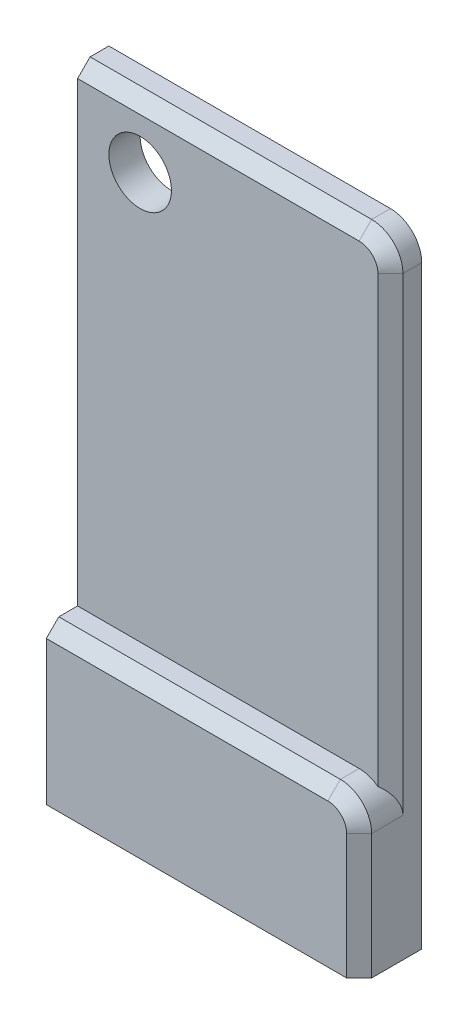
SolidWorks part; units mm, degrees
material "1060 Alloy"
ref_plane "Front Plane" through (0, 0, 0) normal (0, 0, 1) x (1, 0, 0)
ref_plane "Top Plane" through (0, 0, 0) normal (0, 1, 0) x (1, 0, 0)
ref_plane "Right Plane" through (0, 0, 0) normal (1, 0, 0) x (0, 0, -1)
sketch "Sketch1" plane through (0, 0, 0) normal (0, 0, 1) x (1, 0, 0)
  line L1 (-200, 460.7143) -> (300, 460.7143)
  line L2 (-200, 460.7143) -> (-200, -539.2857)
  line L3 (-200, -539.2857) -> (300, -539.2857)
  line L4 (300, 460.7143) -> (300, -539.2857)
  dimension "D1" = 1000
  dimension "D2" = 500
extrude "Boss-Extrude1" add sketch "Sketch1" along normal blind 50
sketch "Sketch2" plane through (0, 0, 50) normal (0, 0, 1) x (1, 0, 0)
  line L0 (300, -539.2857) -> (300, 460.7143) construction
  line L1 (-200, -539.2857) -> (300, -539.2857)
  line L2 (-200, -539.2857) -> (-200, -289.2857)
  line L3 (-200, -289.2857) -> (300, -289.2857)
  line L4 (300, -539.2857) -> (300, -289.2857)
  dimension "D1" = 250
extrude "Boss-Extrude2" add sketch "Sketch2" along normal blind 50
sketch "Sketch3" plane through (0, 0, 50) normal (0, 0, 1) x (1, 0, 0)
  line L0 (-200, 460.7143) -> (-200, -289.2857) construction
  line L1 (300, 460.7143) -> (-200, 460.7143) construction
  circle A0 centre (-100, 360.7143) radius 50
  dimension "D1" = 100
  dimension "D2" = 100
  dimension "D3" = 100
extrude "Cut-Extrude1" cut sketch "Sketch3" against normal through all
fillet "Fillet1" radius 50 2 edges at (300, -289.2857, 75) (300, 460.7143, 25)
chamfer "Chamfer1" distance 20 angle 45 6 edges at (300, -439.2857, 100) (285.3553, -303.9304, 100) (25, -289.2857, 100) (300, 35.7143, 50) (285.3553, 446.0696, 50) (25, 460.7143, 50)
shell "Shell1" thickness 10
